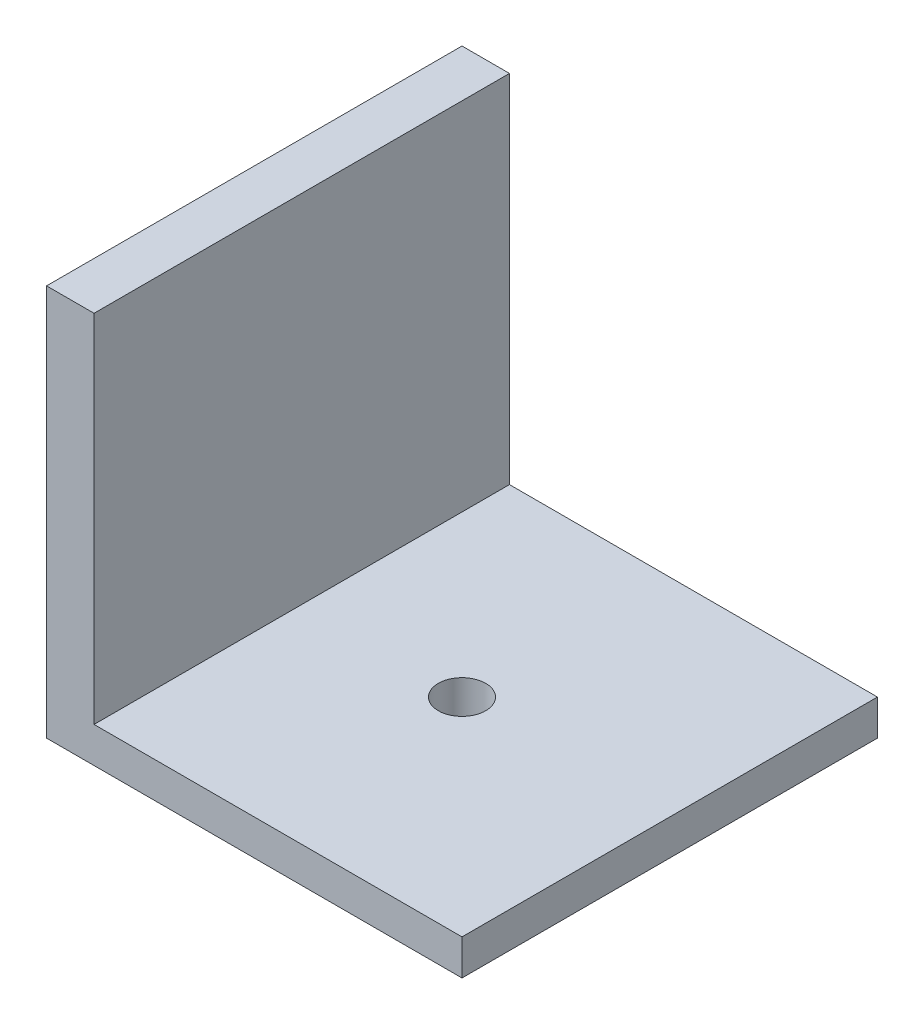
SolidWorks part; units mm, degrees
ref_plane "Front Plane" through (0, 0, 0) normal (0, 0, 1) x (1, 0, 0)
ref_plane "Top Plane" through (0, 0, 0) normal (0, 1, 0) x (1, 0, 0)
ref_plane "Right Plane" through (0, 0, 0) normal (1, 0, 0) x (0, 0, -1)
sketch "Sketch1" plane through (0, 0, 0) normal (0, 1, 0) x (1, 0, 0)
  line L1 (-17.5, -17.5) -> (17.5, -17.5)
  line L2 (-17.5, -17.5) -> (-17.5, 17.5)
  line L3 (-17.5, 17.5) -> (17.5, 17.5)
  line L4 (17.5, -17.5) -> (17.5, 17.5)
  line L5 (-17.5, -17.5) -> (17.5, 17.5) construction
  line L6 (-17.5, 17.5) -> (17.5, -17.5) construction
  circle A0 centre (0, 0) radius 2
  point P0 (0, 0)
  dimension "D3" = 4
  dimension "D1" = 35
  dimension "D2" = 35
extrude "Boss-Extrude1" add sketch "Sketch1" along normal blind 3
sketch "Sketch2" plane through (0, 3, 0) normal (0, 1, 0) x (1, 0, 0)
  line L0 (-17.5, -17.5) -> (17.5, -17.5) construction
  line L1 (-17.5, 17.5) -> (-13.5, 17.5)
  line L2 (-17.5, 17.5) -> (-17.5, -17.5)
  line L3 (-17.5, -17.5) -> (-13.5, -17.5)
  line L4 (-13.5, 17.5) -> (-13.5, -17.5)
  dimension "D1" = 4
extrude "Boss-Extrude2" add sketch "Sketch2" along normal blind 30
sketch "Sketch3" plane through (-17.5, 0, 0) normal (-1, 0, 0) x (0, 0, 1)
  line L0 (0, 33) -> (0, 0) construction
  line L1 (-17.5, 33) -> (17.5, 33) construction
  circle A0 centre (0, 16.5) radius 4
  dimension "D1" = 8
extrude "Boss-Extrude3" add sketch "Sketch3" along normal blind 8
